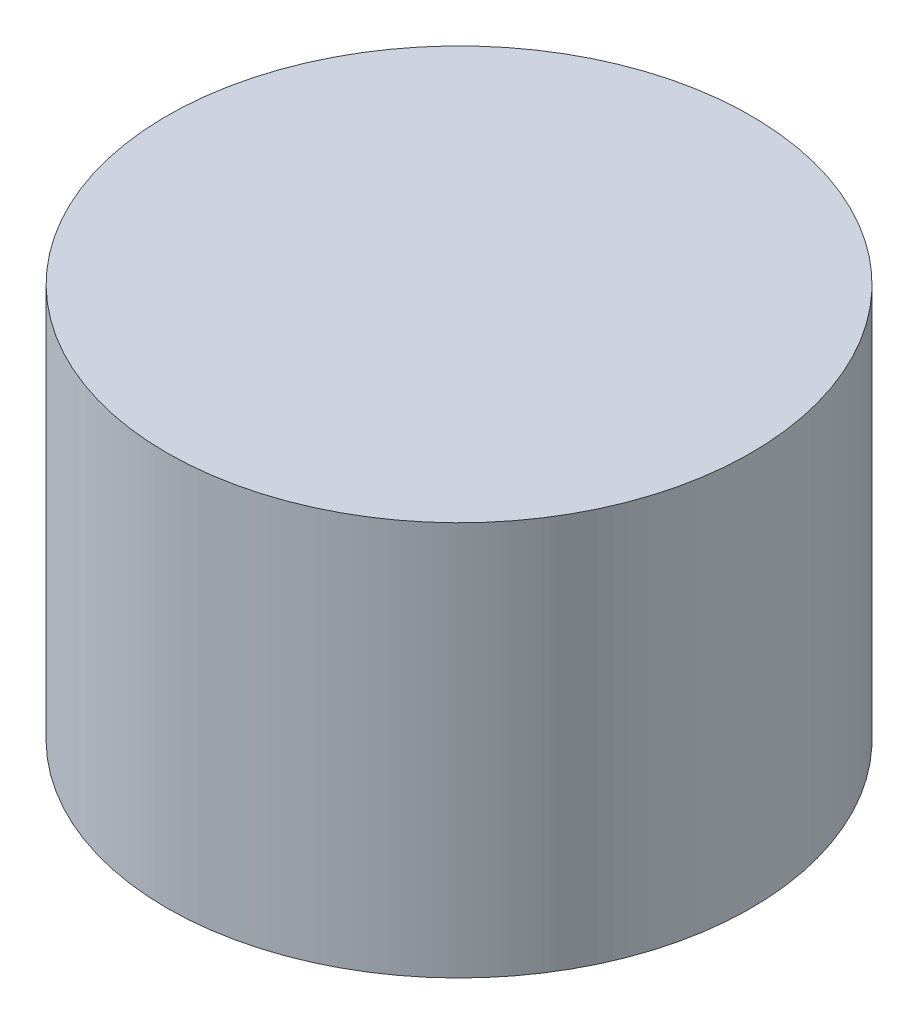
SolidWorks part; units mm, degrees
material "Plain Carbon Steel"
ref_plane "Front Plane" through (0, 0, 0) normal (0, 0, 1) x (1, 0, 0)
ref_plane "Top Plane" through (0, 0, 0) normal (0, 1, 0) x (1, 0, 0)
ref_plane "Right Plane" through (0, 0, 0) normal (1, 0, 0) x (0, 0, -1)
sketch "Sketch1" plane through (0, 0, 0) normal (0, 1, 0) x (1, 0, 0)
  circle A0 centre (0, 0) radius 20
  dimension "D1" = 40
extrude "Boss-Extrude1" add sketch "Sketch1" along normal blind 27
sketch "Sketch2" plane through (0, 0, 0) normal (0, -1, 0) x (1, 0, 0)
  circle A0 centre (0, 13) radius 1.5
  circle A1 centre (11.2583, -6.5) radius 1.5
  circle A2 centre (-11.2583, -6.5) radius 1.5
  point P9 (0, 0)
  dimension "D1" = 3
  dimension "D2" = 13
  dimension "D3" = 3
extrude "Cut-Extrude1" cut sketch "Sketch2" against normal blind 6
